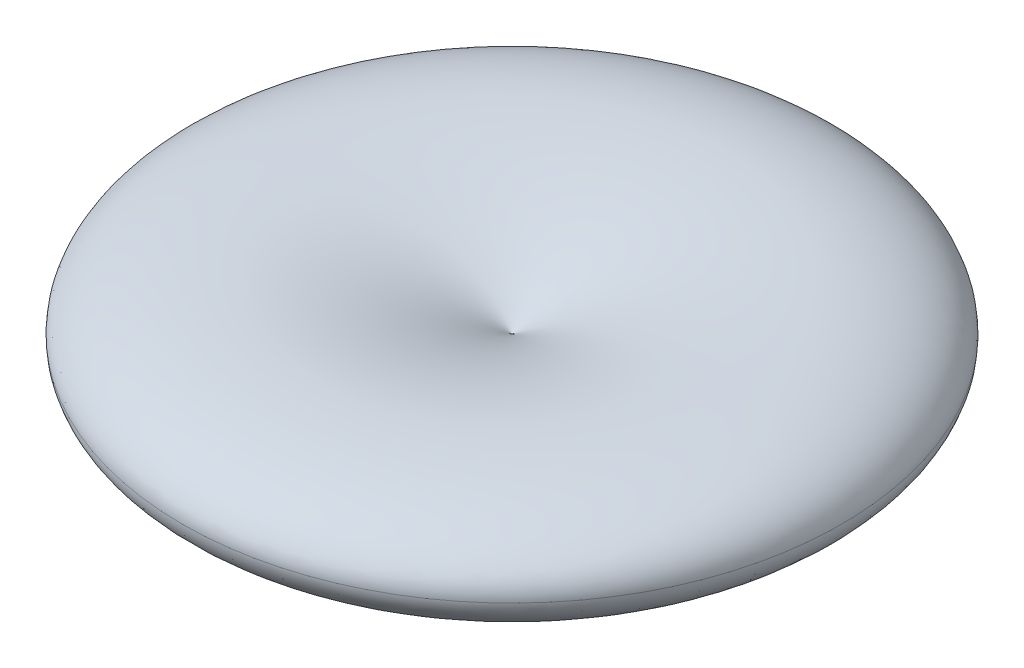
SolidWorks part; units mm, degrees
ref_plane "Front Plane" through (0, 0, 0) normal (0, 0, 1) x (1, 0, 0)
ref_plane "Top Plane" through (0, 0, 0) normal (0, 1, 0) x (1, 0, 0)
ref_plane "Right Plane" through (0, 0, 0) normal (1, 0, 0) x (0, 0, -1)
sketch "Sketch" plane through (0, 0, 0) normal (0, 0, 1) x (1, 0, 0)
  line L0 (0, 0) -> (0, -0.0015) construction
  line L1 (-0.0065, -1000.0496) -> (-0.0065, 48999.9504) construction
  spline S0 degree 4 poles (97.0425, 5.9803) (97.21, 5.7823) (97.5348, 5.3777) (97.9594, 4.786) (98.438, 3.9804) (98.7712, 3.2845) (98.9916, 2.7202) (99.1421, 2.253) (99.2413, 1.8899) (99.3215, 1.5328) (99.3837, 1.1811) (99.4234, 0.8811) (99.4473, 0.631) (99.4638, 0.3737) (99.4727, 0.1197) (99.4732, -0.1227) (99.4626, -0.4089) (99.4466, -0.6357) (99.4248, -0.8586) (99.3857, -1.1727) (99.3092, -1.6172) (99.1686, -2.1918) (98.9479, -2.8532) (98.6547, -3.5436) (98.2819, -4.2555) (97.8059, -5.0111) (97.2161, -5.797) (96.5024, -6.6092) (95.6581, -7.4333) (94.6212, -8.3123) (93.3773, -9.2191) (91.5858, -10.3444) (88.4805, -11.9391) (83.9454, -13.6419) (77.9371, -15.1274) (70.9236, -16.1131) (63.7546, -16.5184) (56.5765, -16.4189) (49.4194, -15.8734) (42.3056, -14.9206) (35.2538, -13.5859) (28.2817, -11.8835) (21.4084, -9.8177) (15.5012, -7.6856) (10.5349, -5.6104) (6.6497, -3.776) (4.1126, -2.4622) (2.2507, -1.4127) (1.0381, -0.6786) (0.4404, -0.2976) (0.1458, -0.1007) (0, 0) knots 0 0 0 0 0 0.008975 0.017951 0.025169 0.032387 0.035642 0.038897 0.042152 0.045407 0.048313 0.05122 0.052674 0.054127 0.057034 0.05962 0.062206 0.063499 0.064792 0.067377 0.073217 0.079056 0.085262 0.091468 0.099151 0.106834 0.116135 0.125437 0.136531 0.147626 0.163142 0.178658 0.20969 0.26825 0.330314 0.392377 0.454441 0.516505 0.578568 0.640632 0.702696 0.764759 0.826823 0.888886 0.919918 0.95095 0.975475 0.987737 0.993869 1 1 1 1 1 construction
  spline S1 degree 4 poles (99.4718, 0) (99.4718, -0.0705) (99.4699, -0.2115) (99.4626, -0.4089) (99.4466, -0.6357) (99.4248, -0.8586) (99.3857, -1.1727) (99.3092, -1.6172) (99.1686, -2.1918) (98.9479, -2.8532) (98.6547, -3.5436) (98.2819, -4.2555) (97.8059, -5.0111) (97.2161, -5.797) (96.5024, -6.6092) (95.6581, -7.4333) (94.6212, -8.3123) (93.3773, -9.2191) (91.5858, -10.3444) (88.4805, -11.9391) (83.9454, -13.6419) (77.9371, -15.1274) (70.9236, -16.1131) (63.7546, -16.5184) (56.5765, -16.4189) (49.4194, -15.8734) (42.3056, -14.9206) (35.2538, -13.5859) (28.2817, -11.8835) (21.4084, -9.8177) (15.5012, -7.6856) (10.5349, -5.6104) (6.6497, -3.776) (4.1126, -2.4622) (2.2507, -1.4127) (1.0381, -0.6786) (0.4404, -0.2976) (0.1458, -0.1007) (0, 0) knots 0.057034 0.057034 0.057034 0.057034 0.057034 0.05962 0.062206 0.063499 0.064792 0.067377 0.073217 0.079056 0.085262 0.091468 0.099151 0.106834 0.116135 0.125437 0.136531 0.147626 0.163142 0.178658 0.20969 0.26825 0.330314 0.392377 0.454441 0.516505 0.578568 0.640632 0.702696 0.764759 0.826823 0.888886 0.919918 0.95095 0.975475 0.987737 0.993869 1 1 1 1 1
  spline S2 degree 4 poles (0, 0) (0.1454, 0.1003) (0.4389, 0.2966) (1.0345, 0.6763) (2.2429, 1.4081) (4.099, 2.4548) (6.6285, 3.7654) (10.5026, 5.5959) (15.4554, 7.6676) (21.3464, 9.7968) (28.2009, 11.8611) (35.1539, 13.5638) (42.1864, 14.9008) (49.2809, 15.8582) (56.4188, 16.4111) (63.5783, 16.5212) (70.7294, 16.1308) (77.7626, 15.1609) (83.7942, 13.6885) (88.7775, 11.8371) (92.1719, 10.0354) (94.1899, 8.6677) (95.5801, 7.5041) (96.4374, 6.6773) (97.1628, 5.8625) (97.6952, 5.1621) (98.0889, 4.5628) (98.4017, 4.0246) (98.6666, 3.5088) (98.9206, 2.9237) (99.1194, 2.3454) (99.2535, 1.8468) (99.354, 1.3679) (99.4146, 0.9764) (99.4534, 0.5957) (99.4685, 0.2607) (99.4732, 0.0188) (99.47, -0.2232) (99.458, -0.5113) (99.428, -0.8491) (99.3819, -1.1929) (99.3024, -1.6381) (99.1936, -2.0857) (99.0219, -2.6438) (98.767, -3.2939) (98.4341, -3.9875) (97.9565, -4.7902) (97.5331, -5.3798) (97.2095, -5.783) (97.0425, -5.9803) knots 0 0 0 0 0 0.00611 0.012221 0.024442 0.048884 0.079836 0.110788 0.172691 0.234595 0.296499 0.358403 0.420307 0.482211 0.544115 0.606019 0.667923 0.729826 0.789465 0.820417 0.851369 0.862509 0.873649 0.8831 0.892551 0.900225 0.904061 0.907898 0.914088 0.920279 0.926115 0.929034 0.931952 0.937194 0.939815 0.942436 0.942966 0.945905 0.948843 0.951782 0.954721 0.957969 0.964466 0.967714 0.974913 0.982113 0.991056 1 1 1 1 1 construction
  spline S3 degree 4 poles (0, 0) (0.1454, 0.1003) (0.4389, 0.2966) (1.0345, 0.6763) (2.2429, 1.4081) (4.099, 2.4548) (6.6285, 3.7654) (10.5026, 5.5959) (15.4554, 7.6676) (21.3464, 9.7968) (28.2009, 11.8611) (35.1539, 13.5638) (42.1864, 14.9008) (49.2809, 15.8582) (56.4188, 16.4111) (63.5783, 16.5212) (70.7294, 16.1308) (77.7626, 15.1609) (83.7942, 13.6885) (88.7775, 11.8371) (92.1719, 10.0354) (94.1899, 8.6677) (95.5801, 7.5041) (96.4374, 6.6773) (97.1628, 5.8625) (97.6952, 5.1621) (98.0889, 4.5628) (98.4017, 4.0246) (98.6666, 3.5088) (98.9206, 2.9237) (99.1194, 2.3454) (99.2535, 1.8468) (99.354, 1.3679) (99.4146, 0.9764) (99.4534, 0.5957) (99.4685, 0.2607) (99.4716, 0.1004) (99.4718, 0.0144) (99.4718, 0) knots 0 0 0 0 0 0.00611 0.012221 0.024442 0.048884 0.079836 0.110788 0.172691 0.234595 0.296499 0.358403 0.420307 0.482211 0.544115 0.606019 0.667923 0.729826 0.789465 0.820417 0.851369 0.862509 0.873649 0.8831 0.892551 0.900225 0.904061 0.907898 0.914088 0.920279 0.926115 0.929034 0.931952 0.937194 0.939815 0.942436 0.942966 0.942966 0.942966 0.942966 0.942966
revolve "Revolve" add sketch "Sketch" angle 360 about L1
